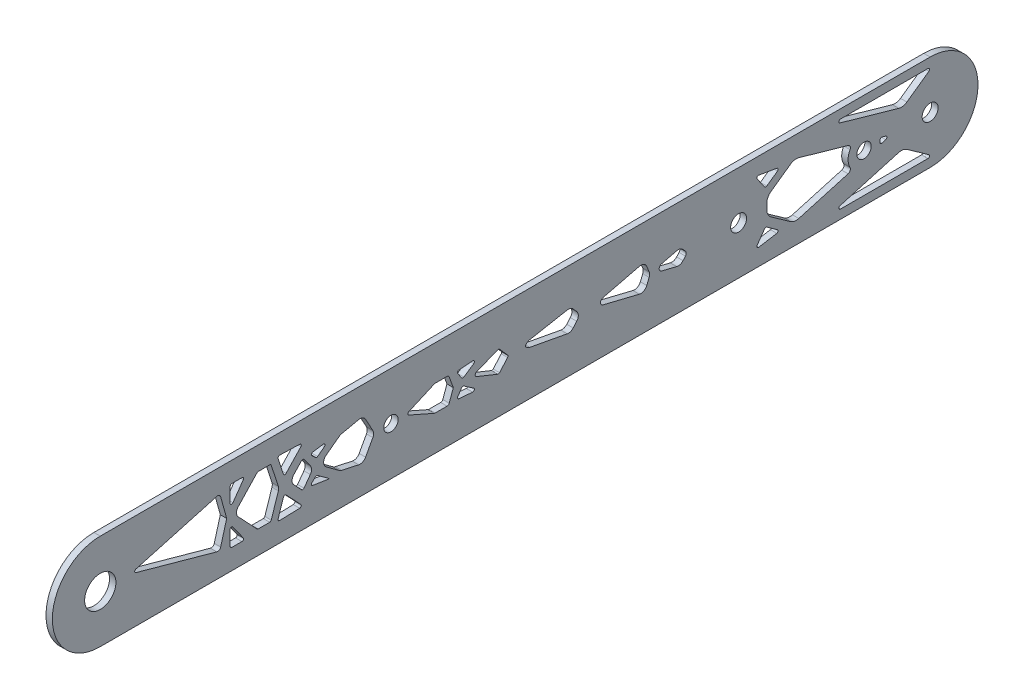
SolidWorks part; units mm, degrees
ref_plane "Front Plane" through (0, 0, 0) normal (0, 0, 1) x (1, 0, 0)
ref_plane "Top Plane" through (0, 0, 0) normal (0, 1, 0) x (1, 0, 0)
ref_plane "Right Plane" through (0, 0, 0) normal (1, 0, 0) x (0, 0, -1)
sketch "Sketch1" plane through (0, 0, 0) normal (1, 0, 0) x (0, 0, -1)
  line L0 (-200, 15) -> (0, 15)
  line L1 (-200, -15) -> (0, -15)
  line L2 (0, -15) -> (60, -15)
  line L3 (60, 15) -> (0, 15)
  line L4 (15, 0) -> (-15, 0) construction
  circle A0 centre (0, 0) radius 15
  circle A1 centre (60, 0) radius 15
  circle A2 centre (-200, 0) radius 15
  circle A3 centre (0, 0) radius 2.5
  circle A4 centre (60, 0) radius 2.5
  circle A5 centre (-200, 0) radius 4.9
  dimension "D1" = 30
  dimension "D3" = 30
  dimension "D5" = 30
  dimension "D6" = 5
  dimension "D7" = 5
  dimension "D8" = 9.8
  dimension "D2" = 60
  dimension "D4" = 200
extrude "Boss-Extrude1" add sketch "Sketch1" along normal blind 2 contours A2 L1 A0 L0 | A0 L4 A3 L2 | L4 A0 A3 | A1 L3 A0 L2 | A1 A4 | A2 A5
sketch "Sketch6" plane through (2, 0, 0) normal (1, 0, 0) x (0, 0, -1)
  line L0 (-188.8522, 0.4818) -> (-163.512, 7.5165)
  line L1 (-162.2809, 6.8204) -> (-160.3875, 0)
  line L2 (-160.3875, 0) -> (-190.5877, 0)
  line L3 (-158.7819, 8.6644) -> (-155.6112, 8.6644)
  line L4 (-155.2027, 7.876) -> (-158.4411, 3.2883)
  line L5 (-159.3495, 3.584) -> (-159.2818, 8.1717)
  line L6 (-156.7711, 1.3722) -> (-150.8723, 7.627)
  line L7 (-150.5085, 7.784) -> (-146.9101, 7.784)
  line L8 (-146.4349, 7.4393) -> (-144.2059, 0.6215)
  line L9 (-144.0027, 0) -> (-158.0652, 0)
  line L10 (-144.2891, 8.2147) -> (-142.622, 3.1155)
  line L11 (-141.783, 2.9278) -> (-137.1604, 7.8293)
  line L12 (-137.5085, 8.6721) -> (-143.7981, 8.8698)
  line L13 (-139.364, 1.3722) -> (-136.9419, 3.9405)
  line L14 (-136.1753, 3.8936) -> (-134.1834, 1.1848)
  line L15 (-133.3121, 0) -> (-140.6581, 0)
  line L16 (-133.6879, 3.6712) -> (-132.5554, 2.6032)
  line L17 (-131.9161, 2.5641) -> (-129.8001, 4.1201)
  line L18 (-130.1705, 5.0174) -> (-133.4191, 4.5294)
  line L19 (-103.3483, 0.4326) -> (-95.3545, 3.9484)
  line L20 (-129.2033, 1.6082) -> (-125.1184, 4.6281)
  line L21 (-124.353, 4.9746) -> (-119.0548, 6.1225)
  line L22 (-116.8768, 5.1278) -> (-114.5964, 0.96)
  line L23 (-114.0711, 0) -> (-130.9191, 0)
  line L24 (-116.8768, -5.1278) -> (-114.5964, -0.96)
  line L25 (-124.353, -4.9746) -> (-119.0548, -6.1225)
  line L26 (-129.2033, -1.6082) -> (-125.1184, -4.6281)
  line L27 (-95.0727, 4.0076) -> (-91.3437, 4.0076)
  line L28 (-128.1715, -5.3177) -> (-133.4191, -4.5294)
  line L29 (-131.9161, -2.5641) -> (-128.1715, -5.3177)
  line L30 (-133.6879, -3.6712) -> (-132.5554, -2.6032)
  line L31 (-136.1753, -3.8936) -> (-134.1834, -1.1848)
  line L32 (-139.364, -1.3722) -> (-136.9419, -3.9405)
  line L33 (-137.5085, -8.6721) -> (-143.7981, -8.8698)
  line L34 (-141.783, -2.9278) -> (-137.1604, -7.8293)
  line L35 (-144.2891, -8.2147) -> (-142.622, -3.1155)
  line L36 (-146.4349, -7.4393) -> (-144.2059, -0.6215)
  line L37 (-150.5085, -7.784) -> (-146.9101, -7.784)
  line L38 (-156.7711, -1.3722) -> (-150.8723, -7.627)
  line L39 (-159.3495, -3.584) -> (-159.2818, -8.1717)
  line L40 (-155.2027, -7.876) -> (-158.4411, -3.2883)
  line L41 (-158.7819, -8.6644) -> (-155.6112, -8.6644)
  line L42 (-162.2809, -6.8204) -> (-160.3875, 0)
  line L43 (-188.8522, -0.4818) -> (-163.512, -7.5165)
  line L44 (-90.6858, 3.5469) -> (-89.386, -0.0251)
  line L45 (-87.9837, 3.0945) -> (-86.7724, 1.3225)
  line L46 (-86.0775, 1.1919) -> (-83.0008, 3.2952)
  line L47 (-83.3215, 4.2065) -> (-87.6095, 3.8752)
  line L48 (-82.085, 0.6243) -> (-75.4597, 3.2918)
  line L49 (-74.8983, 3.159) -> (-72.3775, 0.3059)
  line L50 (-72.0851, -0.0251) -> (-83.6982, -0.0251)
  line L51 (-66.6012, 0.3496) -> (-66.3812, 0.544)
  line L52 (-65.4241, 1.0112) -> (-53.7094, 3.199)
  line L53 (-51.8434, 2.5572) -> (-50.7319, 1.2991)
  line L54 (-49.5619, -0.0251) -> (-67.0253, -0.0251)
  line L55 (-16.6638, 0.637) -> (-17.4188, 1.4916)
  line L56 (-19.3939, 2.1098) -> (-24.1399, 0.9461)
  line L57 (-28.101, -0.0251) -> (-16.0788, -0.0251)
  line L58 (-28.0338, 0.7218) -> (-28.7728, 2.5572)
  line L59 (-31.1048, 3.7526) -> (-42.5387, 0.9461)
  line L60 (-46.4954, -0.0251) -> (-27.7331, -0.0251)
  line L61 (-31.1048, -3.8028) -> (-42.5387, -0.9963)
  line L62 (-28.0338, -0.7721) -> (-28.7728, -2.6074)
  line L63 (-19.3939, -2.16) -> (-24.1399, -0.9963)
  line L64 (-16.6638, -0.6872) -> (-17.4188, -1.5418)
  line L65 (-51.8434, -2.6074) -> (-50.7319, -1.3493)
  line L66 (-65.4241, -1.0614) -> (-53.7094, -3.2492)
  line L67 (-66.6012, -0.3998) -> (-66.3812, -0.5942)
  line L68 (-74.8983, -3.2092) -> (-72.3775, -0.3562)
  line L69 (-82.085, -0.6746) -> (-75.4597, -3.342)
  line L70 (-83.3215, -4.2567) -> (-87.6095, -3.9254)
  line L71 (-86.0775, -1.2422) -> (-83.0008, -3.3454)
  line L72 (-87.9837, -3.1447) -> (-86.7724, -1.3728)
  line L73 (-90.6858, -3.5971) -> (-89.386, -0.0251)
  line L74 (-95.0727, -4.0578) -> (-91.3437, -4.0578)
  line L75 (-103.3483, -0.4828) -> (-95.3545, -3.9986)
  line L76 (18.8525, 8.244) -> (46.1013, 0.4809)
  line L77 (47.7891, 0) -> (8.8623, 0)
  line L78 (8.8623, -1.0031) -> (8.8623, 1.0031)
  line L79 (10.1318, 3.4536) -> (16.3, 7.8094)
  line L80 (12.1727, 7.9349) -> (8.8291, 5.5738)
  line L81 (8.1323, 5.6938) -> (5.7996, 8.9972)
  line L82 (6.2899, 9.7788) -> (11.9662, 8.8366)
  line L83 (31.7686, 11.2289) -> (50.1558, 5.9904)
  line L84 (52.7083, 6.425) -> (59.6137, 11.3013)
  line L85 (59.3253, 12.2098) -> (31.9056, 12.2098)
  line L86 (59.3253, -12.2098) -> (31.9056, -12.2098)
  line L87 (52.7083, -6.425) -> (59.6137, -11.3013)
  line L88 (31.7686, -11.2289) -> (50.1558, -5.9904)
  line L89 (6.2899, -9.7788) -> (11.9662, -8.8366)
  line L90 (8.1323, -5.6938) -> (5.7996, -8.9972)
  line L91 (12.1727, -7.9349) -> (8.8291, -5.5738)
  line L92 (10.1318, -3.4536) -> (16.3, -7.8094)
  line L93 (18.8525, -8.244) -> (46.1013, -0.4809)
  arc A0 (-162.2809, 6.8204) -> (-163.512, 7.5165) centre (-163.2445, 6.5529) ccw
  arc A1 (-162.2809, -6.8204) -> (-163.512, -7.5165) centre (-163.2445, -6.5529) cw
  arc A2 (-155.6112, 8.6644) -> (-155.2027, 7.876) centre (-155.6112, 8.1644) cw
  arc A3 (-158.7819, 8.6644) -> (-159.2818, 8.1717) centre (-158.7819, 8.1644) ccw
  arc A4 (-150.8723, 7.627) -> (-150.5085, 7.784) centre (-150.5085, 7.284) cw
  arc A5 (-146.9101, 7.784) -> (-146.4349, 7.4393) centre (-146.9101, 7.284) cw
  arc A6 (-146.4349, -7.4393) -> (-146.9101, -7.784) centre (-146.9101, -7.284) cw
  arc A7 (-150.5085, -7.784) -> (-150.8723, -7.627) centre (-150.5085, -7.284) cw
  arc A8 (-155.2027, -7.876) -> (-155.6112, -8.6644) centre (-155.6112, -8.1644) cw
  arc A9 (-159.2818, -8.1717) -> (-158.7819, -8.6644) centre (-158.7819, -8.1644) ccw
  arc A10 (-158.4411, -3.2883) -> (-159.3495, -3.584) centre (-158.8496, -3.5766) ccw
  arc A11 (-158.4411, 3.2883) -> (-159.3495, 3.584) centre (-158.8496, 3.5766) cw
  arc A12 (-133.4191, -4.5294) -> (-133.6879, -3.6712) centre (-133.3448, -4.035) cw
  arc A13 (-131.9161, -2.5641) -> (-132.5554, -2.6032) centre (-132.2123, -2.9669) ccw
  arc A14 (-129.8001, 4.1201) -> (-130.1705, 5.0174) centre (-130.0963, 4.5229) ccw
  arc A15 (-132.5554, 2.6032) -> (-131.9161, 2.5641) centre (-132.2123, 2.9669) ccw
  arc A16 (-133.6879, 3.6712) -> (-133.4191, 4.5294) centre (-133.3448, 4.035) cw
  arc A17 (-125.1184, 4.6281) -> (-124.353, 4.9746) centre (-123.9295, 3.0199) cw
  arc A18 (-124.353, -4.9746) -> (-125.1184, -4.6281) centre (-123.9295, -3.0199) cw
  arc A19 (-116.8768, -5.1278) -> (-119.0548, -6.1225) centre (-118.6313, -4.1678) cw
  arc A20 (-114.5964, 0.96) -> (-114.5964, -0.96) centre (-116.3509, 0) cw
  arc A21 (-116.8768, 5.1278) -> (-119.0548, 6.1225) centre (-118.6313, 4.1678) ccw
  arc A22 (-129.2033, -1.6082) -> (-129.2033, 1.6082) centre (-128.0143, 0) cw
  arc A23 (-144.2059, 0.6215) -> (-144.2059, -0.6215) centre (-146.1069, 0) cw
  arc A24 (-156.7711, -1.3722) -> (-156.7711, 1.3722) centre (-155.3161, 0) cw
  arc A25 (-134.1834, 1.1848) -> (-134.1834, -1.1848) centre (-135.7947, 0) cw
  arc A26 (-139.364, -1.3722) -> (-139.364, 1.3722) centre (-137.909, 0) cw
  arc A27 (-136.1753, -3.8936) -> (-136.9419, -3.9405) centre (-136.5781, -3.5974) cw
  arc A28 (-136.9419, 3.9405) -> (-136.1753, 3.8936) centre (-136.5781, 3.5974) cw
  arc A29 (-137.1604, 7.8293) -> (-137.5085, 8.6721) centre (-137.5242, 8.1723) ccw
  arc A30 (-144.2891, 8.2147) -> (-143.7981, 8.8698) centre (-143.8138, 8.37) cw
  arc A31 (-142.622, 3.1155) -> (-141.783, 2.9278) centre (-142.1467, 3.2708) ccw
  arc A32 (-137.5085, -8.6721) -> (-137.1604, -7.8293) centre (-137.5242, -8.1723) ccw
  arc A33 (-143.7981, -8.8698) -> (-144.2891, -8.2147) centre (-143.8138, -8.37) cw
  arc A34 (-141.783, -2.9278) -> (-142.622, -3.1155) centre (-142.1467, -3.2708) ccw
  arc A35 (-72.3775, 0.3059) -> (-72.3775, -0.3562) centre (-72.7522, -0.0251) cw
  arc A36 (-74.8983, -3.2092) -> (-75.4597, -3.342) centre (-75.273, -2.8782) cw
  arc A37 (-75.4597, 3.2918) -> (-74.8983, 3.159) centre (-75.273, 2.828) cw
  arc A38 (-83.3215, -4.2567) -> (-83.0008, -3.3454) centre (-83.283, -3.7582) ccw
  arc A39 (-87.6095, -3.9254) -> (-87.9837, -3.1447) centre (-87.5709, -3.4269) cw
  arc A40 (-86.0775, -1.2422) -> (-86.7724, -1.3728) centre (-86.3596, -1.6549) ccw
  arc A41 (-83.0008, 3.2952) -> (-83.3215, 4.2065) centre (-83.283, 3.7079) ccw
  arc A42 (-86.7724, 1.3225) -> (-86.0775, 1.1919) centre (-86.3596, 1.6047) ccw
  arc A43 (-87.9837, 3.0945) -> (-87.6095, 3.8752) centre (-87.5709, 3.3766) cw
  arc A44 (-103.3483, 0.4326) -> (-103.3483, -0.4828) centre (-103.147, -0.0251) ccw
  arc A45 (-19.3939, -2.16) -> (-17.4188, -1.5418) centre (-18.9177, -0.2176) ccw
  arc A46 (-17.4188, 1.4916) -> (-19.3939, 2.1098) centre (-18.9177, 0.1673) ccw
  arc A47 (-31.1048, -3.8028) -> (-28.7728, -2.6074) centre (-30.628, -1.8605) ccw
  arc A48 (-28.7728, 2.5572) -> (-31.1048, 3.7526) centre (-30.628, 1.8102) ccw
  arc A49 (-28.0338, 0.7218) -> (-28.0338, -0.7721) centre (-29.8891, -0.0251) cw
  arc A50 (-50.7319, 1.2991) -> (-50.7319, -1.3493) centre (-52.2307, -0.0251) cw
  arc A51 (-51.8434, -2.6074) -> (-53.7094, -3.2492) centre (-53.3422, -1.2832) cw
  arc A52 (-53.7094, 3.199) -> (-51.8434, 2.5572) centre (-53.3422, 1.233) cw
  arc A53 (-65.4241, -1.0614) -> (-66.3812, -0.5942) centre (-65.057, 0.9046) cw
  arc A54 (-66.3812, 0.544) -> (-65.4241, 1.0112) centre (-65.057, -0.9548) cw
  arc A55 (-82.085, 0.6243) -> (-82.085, -0.6746) centre (-81.8236, -0.0251) ccw
  arc A56 (-95.0727, -4.0578) -> (-95.3545, -3.9986) centre (-95.0727, -3.3577) cw
  arc A57 (-90.6858, -3.5971) -> (-91.3437, -4.0578) centre (-91.3437, -3.3577) cw
  arc A58 (-91.3437, 4.0076) -> (-90.6858, 3.5469) centre (-91.3437, 3.3075) cw
  arc A59 (-95.3545, 3.9484) -> (-95.0727, 4.0076) centre (-95.0727, 3.3075) cw
  arc A60 (-24.1399, -0.9963) -> (-24.1399, 0.9461) centre (-23.9018, -0.0251) cw
  arc A61 (-42.5387, -0.9963) -> (-42.5387, 0.9461) centre (-42.3003, -0.0251) cw
  arc A62 (-16.6638, -0.6872) -> (-16.6638, 0.637) centre (-17.4132, -0.0251) ccw
  arc A63 (-66.6012, -0.3998) -> (-66.6012, 0.3496) centre (-66.2702, -0.0251) cw
  arc A64 (46.1013, 0.4809) -> (46.1013, -0.4809) centre (45.9643, 0) cw
  arc A65 (59.3253, -12.2098) -> (59.6137, -11.3013) centre (59.3253, -11.7098) ccw
  arc A66 (59.6137, 11.3013) -> (59.3253, 12.2098) centre (59.3253, 11.7098) ccw
  arc A67 (31.7686, 11.2289) -> (31.9056, 12.2098) centre (31.9056, 11.7098) cw
  arc A68 (31.9056, -12.2098) -> (31.7686, -11.2289) centre (31.9056, -11.7098) cw
  arc A69 (11.9662, -8.8366) -> (12.1727, -7.9349) centre (11.8843, -8.3433) ccw
  arc A70 (6.2899, -9.7788) -> (5.7996, -8.9972) centre (6.208, -9.2856) cw
  arc A71 (8.1323, -5.6938) -> (8.8291, -5.5738) centre (8.5407, -5.9822) cw
  arc A72 (8.8291, 5.5738) -> (8.1323, 5.6938) centre (8.5407, 5.9822) cw
  arc A73 (12.1727, 7.9349) -> (11.9662, 8.8366) centre (11.8843, 8.3433) ccw
  arc A74 (5.7996, 8.9972) -> (6.2899, 9.7788) centre (6.208, 9.2856) cw
  arc A75 (52.7083, -6.425) -> (50.1558, -5.9904) centre (50.9778, -8.8756) ccw
  arc A76 (50.1558, 5.9904) -> (52.7083, 6.425) centre (50.9778, 8.8756) ccw
  arc A77 (8.8623, 1.0031) -> (10.1318, 3.4536) centre (11.8623, 1.0031) cw
  arc A78 (10.1318, -3.4536) -> (8.8623, -1.0031) centre (11.8623, -1.0031) cw
  arc A79 (16.3, -7.8094) -> (18.8525, -8.244) centre (18.0305, -5.3588) ccw
  arc A80 (18.8525, 8.244) -> (16.3, 7.8094) centre (18.0305, 5.3588) ccw
  arc A81 (-188.8522, -0.4818) -> (-188.8522, 0.4818) centre (-188.7185, 0) cw
  point P47 (-154.6462, 8.6644)
  point P50 (-159.2745, 8.6644)
  point P52 (-150.7242, 7.784)
  point P55 (-146.5475, 7.784)
  point P58 (-146.5475, -7.784)
  point P61 (-150.7242, -7.784)
  point P64 (-154.6462, -8.6644)
  point P67 (-159.2745, -8.6644)
  point P70 (-159.3733, -1.9675)
  point P73 (-159.3733, 1.9675)
  point P76 (-134.4359, -4.3767)
  point P79 (-132.252, -2.3171)
  point P82 (-128.1715, 5.3177)
  point P85 (-132.252, 2.3171)
  point P88 (-134.4359, 4.3767)
  point P91 (-124.7729, 4.8836)
  point P94 (-124.7729, -4.8836)
  point P97 (-117.5942, -6.4389)
  point P103 (-117.5942, 6.4389)
  point P120 (-136.5305, -4.3767)
  point P123 (-136.5305, 4.3767)
  point P126 (-136.3985, 8.6372)
  point P129 (-144.5106, 8.8922)
  point P132 (-142.3605, 2.3155)
  point P135 (-136.3985, -8.6372)
  point P138 (-144.5106, -8.8922)
  point P141 (-142.3605, -2.3155)
  point P177 (-75.1321, -3.4739)
  point P180 (-75.1321, 3.4237)
  point P183 (-81.457, -4.4007)
  point P186 (-88.4719, -3.8588)
  point P189 (-86.4902, -0.96)
  point P192 (-81.457, 4.3505)
  point P195 (-86.4902, 0.9098)
  point P198 (-88.4719, 3.8085)
  point P201 (-104.389, -0.0251)
  point P204 (-18.2195, -2.448)
  point P207 (-18.2195, 2.3978)
  point P210 (-29.4205, -4.2162)
  point P213 (-29.4205, 4.166)
  point P222 (-52.5944, -3.4574)
  point P225 (-52.5944, 3.4072)
  point P228 (-65.9672, -0.96)
  point P231 (-65.9672, 0.9098)
  point P237 (-95.2198, -4.0578)
  point P240 (-90.8534, -4.0578)
  point P243 (-90.8534, 4.0076)
  point P246 (-95.2198, 4.0076)
  point P282 (60.9001, -12.2098)
  point P285 (60.9001, 12.2098)
  point P288 (28.3257, 12.2098)
  point P291 (28.3257, -12.2098)
  point P294 (13.1673, -8.6372)
  point P297 (5.1092, -9.9748)
  point P300 (8.4207, -5.2854)
  point P303 (8.4207, 5.2854)
  point P306 (13.1673, 8.6372)
  point P309 (5.1092, 9.9748)
  point P312 (51.536, -5.5972)
  point P315 (51.536, 5.5972)
  point P318 (8.8623, 2.5572)
  point P321 (8.8623, -2.5572)
  point P324 (17.4723, -8.6372)
  point P327 (17.4723, 8.6372)
  dimension "D1" = 1
  dimension "D2" = 0.5
  dimension "D3" = 0.5
  dimension "D4" = 2
  dimension "D5" = 2
  dimension "D6" = 0.5
  dimension "D7" = 0.5
  dimension "D8" = 0.5
  dimension "D9" = 2
  dimension "D10" = 1
  dimension "D11" = 1
  dimension "D12" = 0.5
  dimension "D13" = 0.5
  dimension "D14" = 3
  dimension "D15" = 0.5
extrude "Cut-Extrude1" cut sketch "Sketch6" against normal through all contours A81 L43 A1 L42 L2 | A81 L2 L1 A0 L0 | A11 L4 A2 L3 A3 L5 | L40 A10 L39 A9 L41 A8 | A24 L38 A7 L37 A6 L36 A23 L9 | A24 L9 A23 L8 A5 L7 A4 L6 | L10 A31 L11 A29 L12 A30 | A28 L13 A26 L15 A25 L14 | A27 L31 A25 L15 A26 L32 | L34 A34 L35 A33 L33 A32 | A16 L16 A15 L17 A14 L18 | A22 L26 A18 L25 A19 L24 A20 L23 | A22 L23 A20 L22 A21 L21 A17 L20 | A59 L19 A44 L75 A56 L74 A57 L73 L44 A58 L27 | A43 L45 A42 L46 A41 L47 | L71 A40 L72 A39 L70 A38 | L50 A55 L69 A36 L68 A35 | L48 A55 L50 A35 L49 A37 | A63 L67 A53 L66 A51 L65 A50 L54 | A63 L54 A50 L53 A52 L52 A54 L51 | A61 L61 A47 L62 A49 L57 L60 | A61 L60 L57 A49 L58 A48 L59 | L92 A79 L93 A64 L77 L78 A78 | L76 A80 L79 A77 L78 L77 A64 | A74 L81 A72 L80 A73 L82 | A71 L90 A70 L89 A69 L91 | L87 A75 L88 A68 L86 A65 | L83 A76 L84 A66 L85 A67 | L28 A12 L30 A13 L29 | L63 A60 L56 A46 L55 A62 L64 A45
sketch "Sketch7" plane through (2, 0, 0) normal (1, 0, 0) x (0, 0, -1)
  circle A0 centre (39.2925, 0) radius 2.25
  circle A5 centre (39.2925, 0) radius 5
  dimension "D1" = 4.5
  dimension "D2" = 10
extrude "Boss-Extrude2" add sketch "Sketch7" against normal blind 2
fillet "Fillet1" radius 1 2 edges at (1, -3.4514, -35.6747) (1, 3.4514, -35.6747)
fillet "Fillet2" radius 0.5 2 edges at (1, -1.0265, -44.186) (1, 1.0265, -44.186)
sketch "Sketch8" plane through (2, 0, 0) normal (1, 0, 0) x (0, 0, -1)
  circle A0 centre (-108.9253, 0) radius 5
  circle A1 centre (-108.9253, 0) radius 2.25
  dimension "D1" = 10
  dimension "D2" = 4.5
extrude "Cut-Extrude2" cut sketch "Sketch8" against normal through all contours A1
